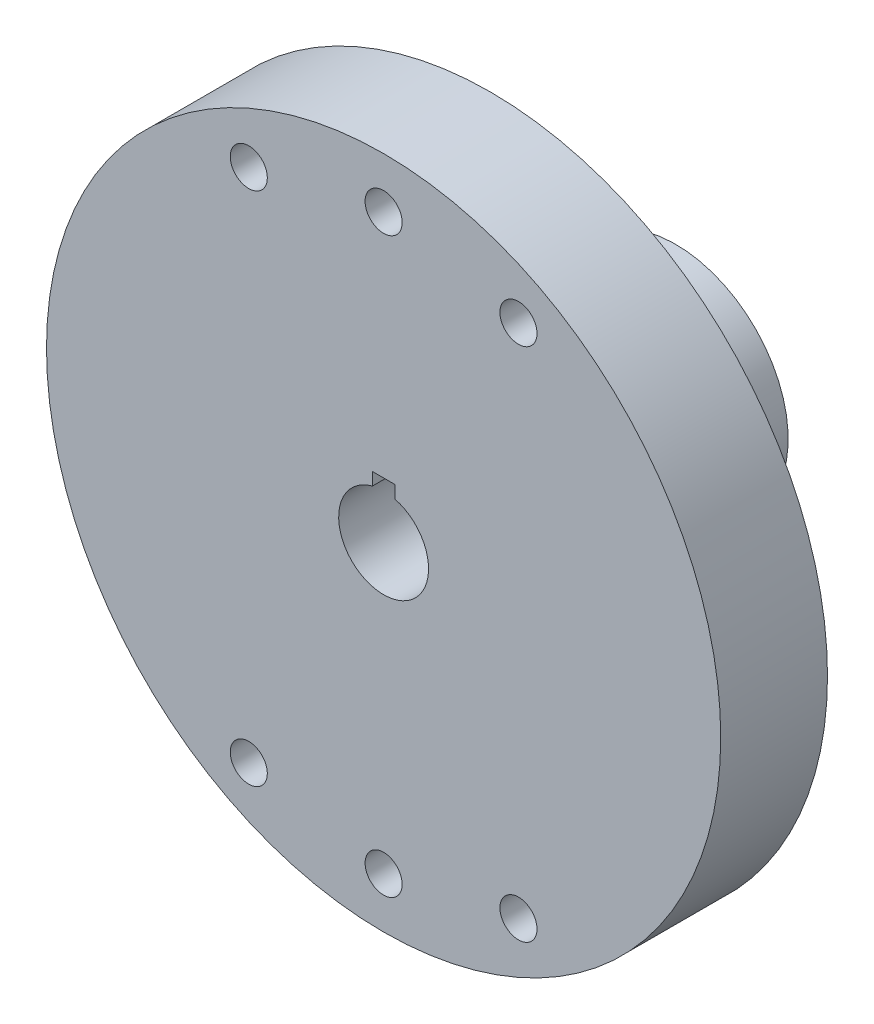
SolidWorks part; units mm, degrees
material "6061 Alloy"
ref_plane "Front" through (0, 0, 0) normal (0, 0, 1) x (1, 0, 0)
ref_plane "Top" through (0, 0, 0) normal (0, 1, 0) x (1, 0, 0)
ref_plane "Right" through (0, 0, 0) normal (1, 0, 0) x (0, 0, -1)
ref_plane "Plane1" through (0, 0, 0) normal (0, -1, 0) x (1, 0, 0)
sketch "Sketch1" plane through (0, 0, 0) normal (0, -1, 0) x (1, 0, 0)
  line L0 (30, 10) -> (0, 10)
  line L1 (0, 10) -> (0, 0.5)
  line L2 (0, 0.5) -> (30, 0.5)
  line L3 (30, 0.5) -> (30, 10)
  line L4 (0, 10) -> (0, 0.5) construction
revolve "Revolve1" add sketch "Sketch1" angle 360 about L4
sketch "Sketch2" plane through (0, 0, 0.5) normal (0, 0, -1) x (-1, 0, 0)
  arc A0 (-14.3793, 22.8525) -> (-14.3793, -22.8525) centre (0, 0) ccw
  arc A1 (-14.3793, -22.8525) -> (-10.5623, -24.8483) centre (-12, -22.95) ccw
  arc A2 (-10.5623, -24.8483) -> (-1.9019, -26.9329) centre (0, 0) ccw
  arc A3 (-1.9019, -26.9329) -> (1.9019, -26.9329) centre (0, -25.5) ccw
  arc A4 (1.9019, -26.9329) -> (10.5623, -24.8483) centre (0, 0) ccw
  arc A5 (10.5623, -24.8483) -> (14.3793, -22.8525) centre (12, -22.95) ccw
  arc A6 (14.3793, -22.8525) -> (14.3793, 22.8525) centre (0, 0) ccw
  arc A7 (14.3793, 22.8525) -> (10.5623, 24.8483) centre (12, 22.95) ccw
  arc A8 (10.5623, 24.8483) -> (1.9019, 26.9329) centre (0, 0) ccw
  arc A9 (1.9019, 26.9329) -> (-1.9019, 26.9329) centre (0, 25.5) ccw
  arc A10 (-1.9019, 26.9329) -> (-10.5623, 24.8483) centre (0, 0) ccw
  arc A11 (-10.5623, 24.8483) -> (-14.3793, 22.8525) centre (-12, 22.95) ccw
extrude "Cut-Extrude1" cut sketch "Sketch2" against normal blind 3.5
sketch "Sketch3" plane through (0, 0, 4) normal (0, 0, -1) x (-1, 0, 0)
  circle A0 centre (0, 0) radius 17.4
extrude "Boss-Extrude1" add sketch "Sketch3" along normal blind 4
sketch "Sketch4" plane through (0, 0, 0) normal (0, 0, -1) x (-1, 0, 0)
  circle A0 centre (0, 0) radius 10
extrude "Boss-Extrude2" add sketch "Sketch4" along normal blind 16
sketch "Sketch5" plane through (0, 0, 10) normal (0, 0, 1) x (1, 0, 0)
  line L0 (-1, 5) -> (-1, 3.873)
  line L1 (1, 3.873) -> (1, 5)
  line L2 (1, 5) -> (-1, 5)
  arc A0 (-1, 3.873) -> (1, 3.873) centre (0, 0) cw
extrude "Cut-Extrude2" cut sketch "Sketch5" against normal through all
sketch "Sketch6" plane through (0, 0, 0) normal (0, -1, 0) x (1, 0, 0)
  line L0 (4, 10) -> (0, 10)
  line L1 (0, 10) -> (0, -16)
  line L2 (0, -16) -> (4, -16)
  line L3 (4, -16) -> (4, 10)
  line L4 (0, 10) -> (0, -16) construction
revolve "Cut-Revolve1" cut sketch "Sketch6" angle 360 about L4
hole_wizard "M4x0.7 Tapped Hole1" positions "Sketch8" profile "Sketch7" tap size "M4x0.7" standard "ANSI Metric" end condition through all
sketch "Sketch8" plane through (0, 0, 10) normal (0, 0, 1) x (1, 0, 0)
  point P0 (-12, -22.95)
  point P1 (0, -25.5)
  point P2 (12, -22.95)
  point P3 (12, 22.95)
  point P4 (0, 25.5)
  point P5 (-12, 22.95)
sketch "Sketch7" plane through (-12, -22.95, 10) normal (1, 0, 0) x (0, -1, 0)
  line L0 (0, 0) -> (0, 26)
  line L1 (0, 26) -> (1.65, 26)
  line L2 (1.65, 26) -> (1.65, 0)
  line L5 (1.65, 0) -> (0, 0)
  line L11 (0, -6.35) -> (0, 107.95) construction
  dimension "Thru Tap Drill Dia." = 3.3
  dimension "Thru Tap Drill Depth" = 26
hole_wizard "M3x0.5 Tapped Hole1" positions "Sketch10" profile "Sketch9" tap size "M3x0.5" standard "ANSI Metric"
sketch "Sketch10" plane through (0, 0, -16) normal (0, 0, -1) x (-1, 0, 0)
  point P0 (-5.0558, -5.0558)
  point P1 (5.0558, -5.0558)
  point P2 (5.0558, 5.0558)
  point P3 (-5.0558, 5.0558)
sketch "Sketch9" plane through (5.0558, -5.0558, -16) normal (1, 0, 0) x (0, 1, 0)
  line L0 (0, 0) -> (0, 8.2511)
  line L1 (0, 8.2511) -> (1.25, 7.5)
  line L2 (1.25, 7.5) -> (1.25, 0)
  line L5 (1.25, 0) -> (0, 0)
  line L10 (0, 8.2511) -> (-1.25, 7.5) construction
  line L11 (0, -6.35) -> (0, 107.95) construction
  dimension "Tap Drill Dia." = 2.5
  dimension "Tap Drill Depth" = 7.5
  dimension "Drill Angle" = 118
fillet "Fillet1" radius 2 1 edges at (-10, 0, 0)
hole_wizard "M3x0.5 Tapped Hole2" positions "Sketch13" profile "Sketch15" tap size "M3x0.5" standard "ANSI Metric"
sketch "Sketch13" plane through (0, 0, 0) normal (0, 1, 0) x (1, 0, 0)
  line L0 (10, 16) -> (-10, 16) construction
  point P0 (0, 8)
  dimension "D1" = 8
sketch "Sketch15" plane through (0, 0, -8) normal (1, 0, 0) x (0, 0, -1)
  line L0 (0, 0) -> (0, 30)
  line L1 (0, 30) -> (1.25, 30)
  line L2 (1.25, 30) -> (1.25, 0)
  line L5 (1.25, 0) -> (0, 0)
  line L11 (0, -6.35) -> (0, 107.95) construction
  dimension "Thru Tap Drill Dia." = 2.5
  dimension "Thru Tap Drill Depth" = 30
cosmetic thread "Hole Thread1" parameters "D2"=3
